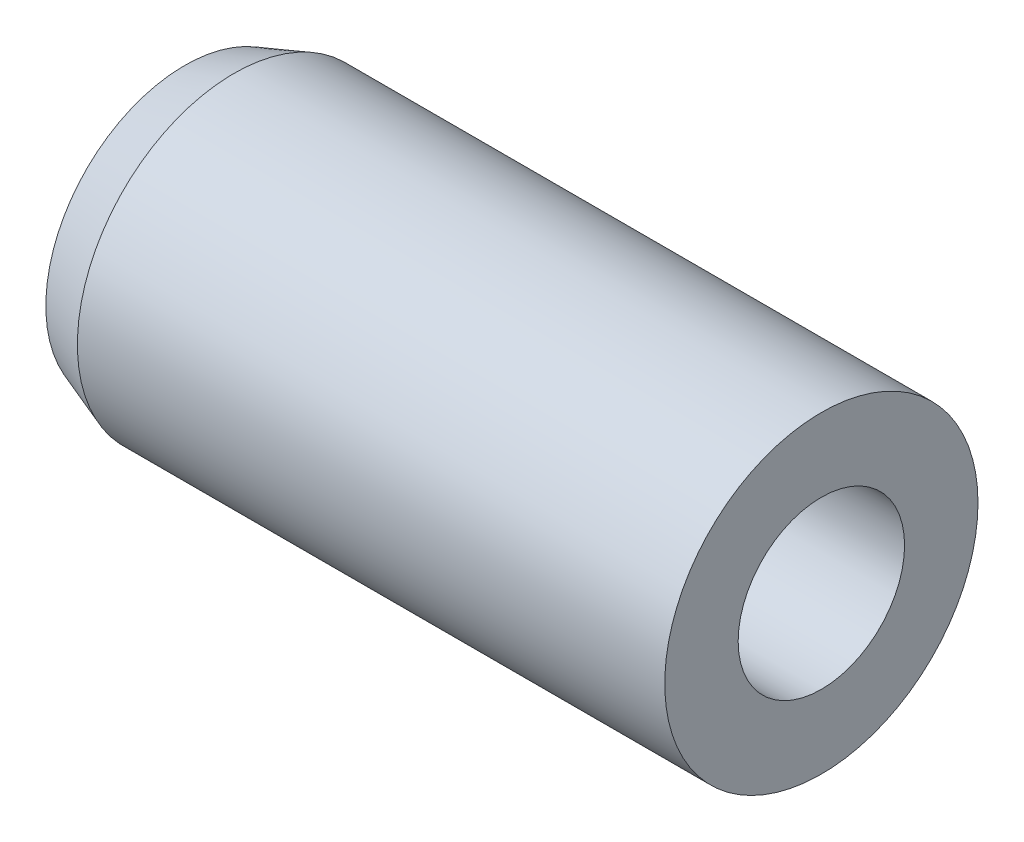
SolidWorks part; units mm, degrees
ref_plane "Alzado" through (0, 0, 0) normal (0, 0, 1) x (1, 0, 0)
ref_plane "Planta" through (0, 0, 0) normal (0, 1, 0) x (1, 0, 0)
ref_plane "Vista lateral" through (0, 0, 0) normal (1, 0, 0) x (0, 0, -1)
sketch "Sketch1" plane through (0, 0, 0) normal (0, 0, 1) x (1, 0, 0)
  line L0 (0, 0) -> (-32.5183, 0)
  line L3 (0, 8) -> (-30, 8)
  line L4 (0, 0) -> (0, 8)
  line L25 (-30, 8) -> (-32.5183, 7.0929)
  line L26 (-32.5183, 7.0929) -> (-32.5183, 0)
  dimension "D1" = 8
revolve "Revolve1" add sketch "Sketch1" angle 360 about L0
cosmetic thread "Rosca cosmética1" parameters "D1"=12, "D2"=10
hole_wizard "Taladro roscado M101" positions "Croquis2" profile "Croquis1" tap size "M10" standard "DIN"
sketch "Croquis2" plane through (0, 0, 0) normal (1, 0, 0) x (0, 0, -1)
  point P0 (0, 0)
sketch "Croquis1" plane through (0, 0, 0) normal (0, 1, 0) x (0, 0, -1)
  line L0 (0, 0) -> (0, 17.5537)
  line L1 (0, 17.5537) -> (4.25, 15)
  line L2 (4.25, 15) -> (4.25, 0)
  line L5 (4.25, 0) -> (0, 0)
  line L10 (0, 17.5537) -> (-4.25, 15) construction
  line L11 (0, -6.35) -> (0, 107.95) construction
  dimension "Diámetro de perforador para roscar" = 8.5
  dimension "Profundidad de perforador para roscar" = 15
  dimension "Ángulo de perforador" = 118
sketch "Croquis3" plane through (-32.5183, 0, 0) normal (-1, 0, 0) x (0, 0, 1)
  line L1 (0, -3.1568) -> (2.7338, -1.5784)
  line L2 (2.7338, -1.5784) -> (2.7338, 1.5784)
  line L3 (2.7338, 1.5784) -> (0, 3.1568)
  line L4 (0, 3.1568) -> (-2.7338, 1.5784)
  line L5 (-2.7338, 1.5784) -> (-2.7338, -1.5784)
  line L6 (-2.7338, -1.5784) -> (0, -3.1568)
  circle A0 centre (0, 0) radius 2.7338 construction
  dimension "D1" = 3.1568
extrude "Cortar-Extruir1" cut sketch "Croquis3" against normal blind 5
